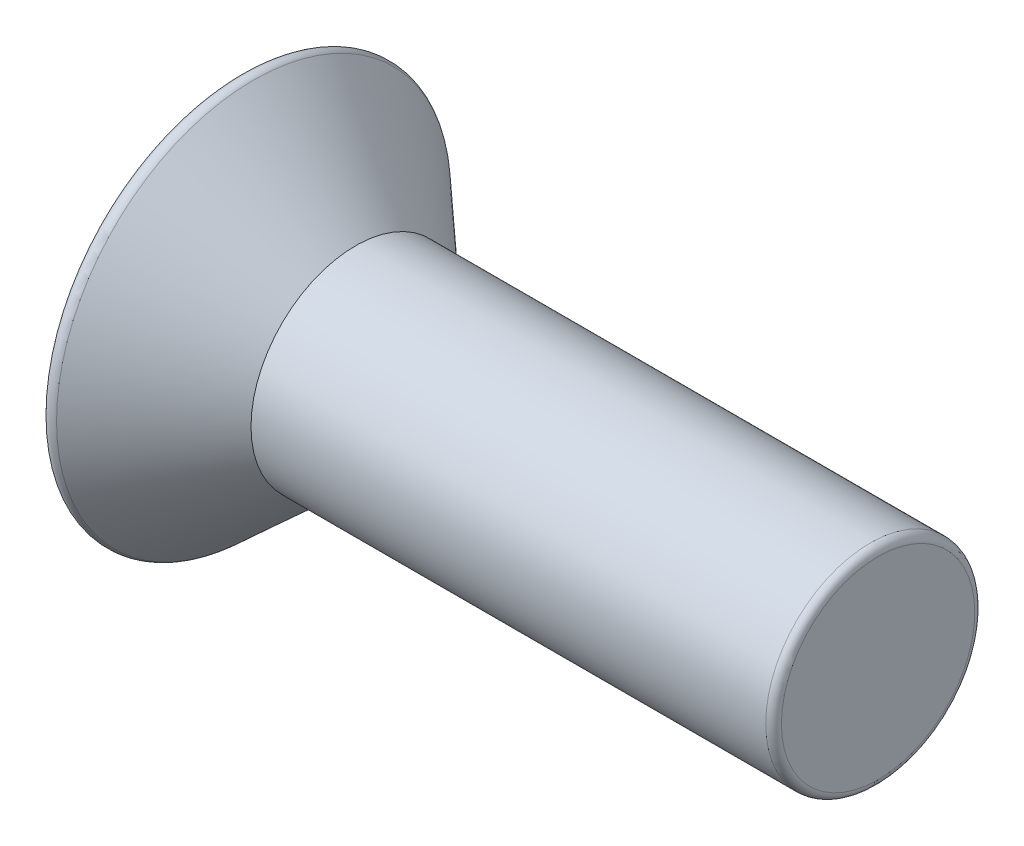
SolidWorks part; units mm, degrees
material "1.0044 (S275JR)"
ref_plane "Ön Düzlem" through (0, 0, 0) normal (0, 0, 1) x (1, 0, 0)
ref_plane "Üst Düzlem" through (0, 0, 0) normal (0, 1, 0) x (1, 0, 0)
ref_plane "Sağ Düzlem" through (0, 0, 0) normal (1, 0, 0) x (0, 0, -1)
sketch "Çizim1" plane through (0, 0, 0) normal (0, 0, 1) x (1, 0, 0)
  line L0 (0, 0) -> (0, 4)
  line L1 (0, 4) -> (-20, 4)
  line L2 (-20, 4) -> (-24.4, 8)
  line L3 (-24.4, 8) -> (-24.4, 0)
  line L4 (-24.4, 0) -> (0, 0)
  dimension "D1" = 4
  dimension "D2" = 20
  dimension "D3" = 8
  dimension "D4" = 4.4
revolve "Döndür1" add sketch "Çizim1" angle 360 about L4
cosmetic thread "Kozmetik Diş Açma1" parameters "D2"=6.619
sketch "Çizim2" plane through (-24.4, 0, 0) normal (-1, 0, 0) x (0, 0, 1)
  line L1 (2.8868, 0) -> (1.4434, 2.5)
  line L2 (1.4434, 2.5) -> (-1.4434, 2.5)
  line L3 (-1.4434, 2.5) -> (-2.8868, 0)
  line L4 (-2.8868, 0) -> (-1.4434, -2.5)
  line L5 (-1.4434, -2.5) -> (1.4434, -2.5)
  line L6 (1.4434, -2.5) -> (2.8868, 0)
  circle A0 centre (0, 0) radius 2.5 construction
  dimension "D1" = 5
extrude "Kes-Ekstrüzyon1" cut sketch "Çizim2" against normal blind 5
fillet "Radyus2" radius 0.3 2 edges at (0, 0, 4) (-24.4, 0, 8)
